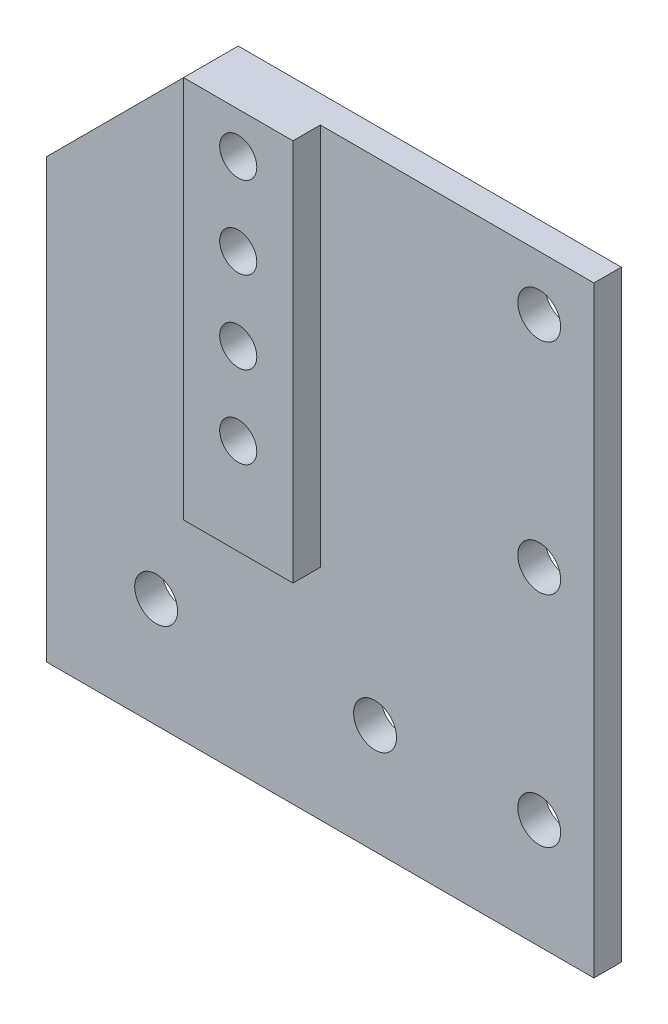
SolidWorks part; units mm, degrees
material "6061 Alloy"
ref_plane "Front Plane" through (0, 0, 0) normal (0, 0, 1) x (1, 0, 0)
ref_plane "Top Plane" through (0, 0, 0) normal (0, 1, 0) x (1, 0, 0)
ref_plane "Right Plane" through (0, 0, 0) normal (1, 0, 0) x (0, 0, -1)
sketch "Sketch1" plane through (0, 0, 0) normal (0, 0, 1) x (1, 0, 0)
  line L15 (-266.7, -12.7) -> (-266.7, 57.15)
  line L16 (-266.7, 609.6) -> (-266.7, -16.7024) construction
  line L18 (-279.4, -12.7) -> (-266.7, -12.7)
  line L19 (-279.4, -12.7) -> (-330.2, -12.7)
  line L20 (-330.2, -12.7) -> (-330.2, 12.7)
  line L21 (-330.2, 12.7) -> (-330.2, 38.1)
  line L22 (-311.15, 57.15) -> (-330.2, 38.1)
  line L23 (-279.4, 57.15) -> (-311.15, 57.15)
  line L24 (-266.7, 57.15) -> (-279.4, 57.15)
  dimension "D1" = 69.85
  dimension "D2" = 50.8
  dimension "D3" = 12.7
extrude "Boss-Extrude1" add sketch "Sketch1" along normal blind 3.175
sketch "Sketch2" plane through (0, 0, 3.175) normal (0, 0, 1) x (1, 0, 0)
  line L0 (-787.4, 12.7) -> (-695.198, 12.7) construction
  line L1 (-787.4, -12.7) -> (-695.198, -12.7) construction
  line L10 (-273.05, 25.4) -> (-273.05, 50.8) construction
  line L11 (-273.05, 0) -> (-273.05, 25.4) construction
  line L12 (-273.05, -12.7) -> (-273.05, 0) construction
  line L13 (-279.4, -12.7) -> (-266.7, -12.7) construction
  line L14 (-330.2, 0) -> (-317.5, 0) construction
  line L15 (-317.5, 0) -> (-292.1, 0) construction
  line L16 (-330.2, -12.7) -> (-330.2, 12.7) construction
  dimension "D1" = 12.7
  dimension "D2" = 25.4
  dimension "D3" = 25.4
  dimension "D4" = 12.7
  dimension "D5" = 25.4
  dimension "D6" = 12.7
  dimension "D7" = 19.05
hole_wizard "#10 Clearance Hole1" positions "Sketch3" profile "Sketch4" hole size "#10" standard "ANSI Inch" end condition through all
sketch "Sketch3" plane through (0, 0, 3.175) normal (0, 0, 1) x (1, 0, 0)
  point P30 (-273.05, 50.8)
  point P33 (-273.05, 25.4)
  point P36 (-273.05, 0)
  point P41 (-317.5, 0)
  point P44 (-292.1, 0)
sketch "Sketch4" plane through (-273.05, 50.8, 3.175) normal (1, 0, 0) x (0, -1, 0)
  line L0 (0, 0) -> (0, 3.175)
  line L1 (0, 3.175) -> (2.4892, 3.175)
  line L2 (2.4892, 3.175) -> (2.4892, 0)
  line L5 (2.4892, 0) -> (0, 0)
  line L11 (0, -6.35) -> (0, 107.95) construction
  dimension "Thru Hole Dia." = 4.9784
  dimension "Thru Hole Depth" = 3.175
sketch "Sketch5" plane through (0, 0, 3.175) normal (0, 0, 1) x (1, 0, 0)
  line L0 (-311.15, 12.7) -> (-298.45, 12.7)
  line L9 (-311.15, 57.15) -> (-311.15, 12.7)
  line L10 (-298.45, 12.7) -> (-298.45, 57.15)
  line L13 (-266.7, 57.15) -> (-311.15, 57.15) construction
  line L17 (-298.45, 57.15) -> (-311.15, 57.15)
  dimension "D1" = 44.45
  dimension "D2" = 12.7
extrude "Boss-Extrude2" add sketch "Sketch5" along normal blind 3.175
sketch "Sketch6" plane through (0, 0, 6.35) normal (0, 0, 1) x (1, 0, 0)
  line L0 (-304.8, 57.15) -> (-304.8, 52.3875) construction
  line L1 (-304.8, 52.3875) -> (-304.8, 42.8625) construction
  line L2 (-304.8, 42.8625) -> (-304.8, 33.3375) construction
  line L4 (-304.8, 33.3375) -> (-304.8, 23.8125) construction
  line L5 (-298.45, 57.15) -> (-311.15, 57.15) construction
  dimension "D1" = 9.525
  dimension "D2" = 4.7625
  dimension "D3" = 9.525
  dimension "D4" = 9.525
hole_wizard "#8 Clearance Hole1" positions "Sketch7" profile "Sketch8" hole size "#8" standard "ANSI Inch" end condition through all
sketch "Sketch7" plane through (0, 0, 6.35) normal (0, 0, 1) x (1, 0, 0)
  point P0 (-304.8, 42.8625)
  point P3 (-304.8, 52.3875)
  point P7 (-304.8, 33.3375)
  point P10 (-304.8, 23.8125)
sketch "Sketch8" plane through (-304.8, 42.8625, 6.35) normal (1, 0, 0) x (0, -1, 0)
  line L0 (0, 0) -> (0, 6.35)
  line L1 (0, 6.35) -> (2.1526, 6.35)
  line L2 (2.1526, 6.35) -> (2.1526, 0)
  line L5 (2.1526, 0) -> (0, 0)
  line L11 (0, -6.35) -> (0, 107.95) construction
  dimension "Thru Hole Dia." = 4.3053
  dimension "Thru Hole Depth" = 6.35
